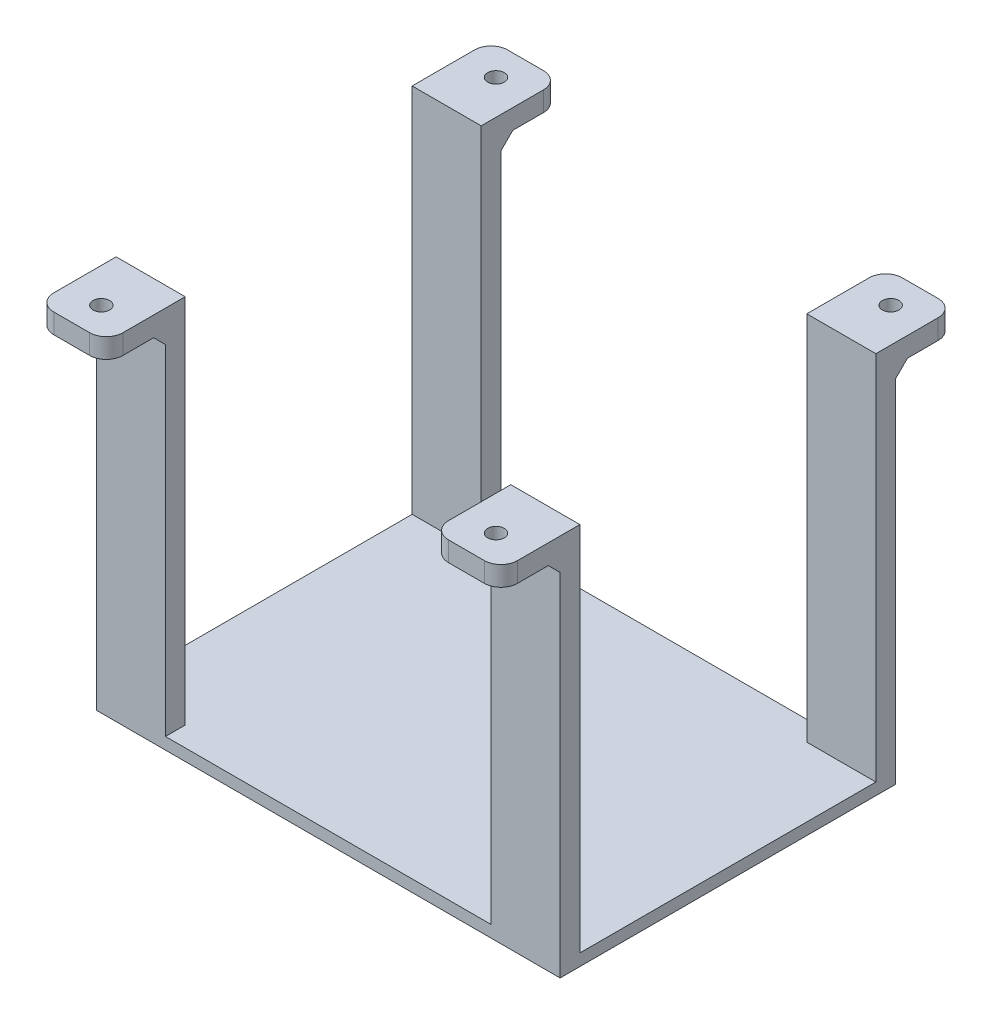
SolidWorks part; units mm, degrees
ref_plane "Front Plane" through (0, 0, 0) normal (0, 0, 1) x (1, 0, 0)
ref_plane "Top Plane" through (0, 0, 0) normal (0, 1, 0) x (1, 0, 0)
ref_plane "Right Plane" through (0, 0, 0) normal (1, 0, 0) x (0, 0, -1)
sketch "Sketch1" plane through (0, 0, 0) normal (0, 1, 0) x (1, 0, 0)
  line L1 (-58.75, 42.5) -> (58.75, 42.5)
  line L2 (-58.75, 42.5) -> (-58.75, -42.5)
  line L3 (-58.75, -42.5) -> (58.75, -42.5)
  line L4 (58.75, 42.5) -> (58.75, -42.5)
  line L5 (-58.75, 42.5) -> (58.75, -42.5) construction
  line L6 (-58.75, -42.5) -> (58.75, 42.5) construction
  point P0 (0, 0)
  dimension "D1" = 85
  dimension "D2" = 117.5
extrude "Boss-Extrude1" add sketch "Sketch1" along normal blind 3
sketch "Sketch2" plane through (0, 3, 0) normal (0, 1, 0) x (1, 0, 0)
  line L0 (0, 69.4551) -> (0, -71.2781) construction
  line L1 (-58.75, 42.5) -> (-41.25, 42.5)
  line L2 (-58.75, 42.5) -> (-58.75, 37.5)
  line L3 (-58.75, 37.5) -> (-41.25, 37.5)
  line L4 (-41.25, 42.5) -> (-41.25, 37.5)
  line L5 (-69.051, 0) -> (66.9053, 0) construction
  line L6 (58.75, 37.5) -> (41.25, 37.5)
  line L7 (41.25, 42.5) -> (41.25, 37.5)
  line L8 (58.75, 42.5) -> (41.25, 42.5)
  line L9 (58.75, 42.5) -> (58.75, 37.5)
  line L10 (58.75, -42.5) -> (58.75, -37.5)
  line L11 (58.75, -42.5) -> (41.25, -42.5)
  line L12 (41.25, -42.5) -> (41.25, -37.5)
  line L13 (58.75, -37.5) -> (41.25, -37.5)
  line L14 (-58.75, -37.5) -> (-41.25, -37.5)
  line L15 (-41.25, -42.5) -> (-41.25, -37.5)
  line L16 (-58.75, -42.5) -> (-41.25, -42.5)
  line L17 (-58.75, -42.5) -> (-58.75, -37.5)
  dimension "D1" = 5
  dimension "D2" = 17.5
extrude "Boss-Extrude2" add sketch "Sketch2" along normal blind 94
sketch "Sketch3" plane through (0, 97, 0) normal (0, 1, 0) x (1, 0, 0)
  line L0 (-41.25, 37.5) -> (-41.25, 42.5) construction
  line L1 (-58.75, 37.5) -> (-41.25, 37.5)
  line L2 (-58.75, 37.5) -> (-58.75, 57.5)
  line L3 (-58.75, 57.5) -> (-41.25, 57.5)
  line L4 (-41.25, 37.5) -> (-41.25, 57.5)
  line L5 (0, 0) -> (0, 99.3222) construction
  line L6 (0, 0) -> (-94.612, 0) construction
  line L7 (58.75, 57.5) -> (41.25, 57.5)
  line L8 (41.25, 37.5) -> (41.25, 57.5)
  line L9 (58.75, 37.5) -> (41.25, 37.5)
  line L10 (58.75, 37.5) -> (58.75, 57.5)
  line L11 (58.75, -37.5) -> (58.75, -57.5)
  line L12 (58.75, -37.5) -> (41.25, -37.5)
  line L13 (41.25, -37.5) -> (41.25, -57.5)
  line L14 (58.75, -57.5) -> (41.25, -57.5)
  line L15 (-58.75, -57.5) -> (-41.25, -57.5)
  line L16 (-41.25, -37.5) -> (-41.25, -57.5)
  line L17 (-58.75, -37.5) -> (-41.25, -37.5)
  line L18 (-58.75, -37.5) -> (-58.75, -57.5)
  circle A0 centre (-50, 50) radius 2.1
  circle A1 centre (50, 50) radius 2.1
  circle A2 centre (50, -50) radius 2.1
  circle A3 centre (-50, -50) radius 2.1
  point P25 (-50, 57.5)
  dimension "D2" = 4.2
  dimension "D1" = 20
  dimension "D3" = 7.5
extrude "Boss-Extrude3" add sketch "Sketch3" against normal blind 5
chamfer "Chamfer1" distance 2 angle 45 4 edges at (-50, 92, 47.9) (50, 92, 52.1) (50, 92, -52.1) (-50, 92, -47.9)
chamfer "Chamfer2" distance 3 angle 45 4 edges at (50, 92, 42.5) (-50, 92, 42.5) (50, 92, -42.5) (-50, 92, -42.5)
fillet "Fillet1" radius 4.2 8 edges at (-41.25, 94.5, 57.5) (-58.75, 94.5, 57.5) (41.25, 94.5, 57.5) (58.75, 94.5, 57.5) (-58.75, 94.5, -57.5) (-41.25, 94.5, -57.5) (41.25, 94.5, -57.5) (58.75, 94.5, -57.5)
